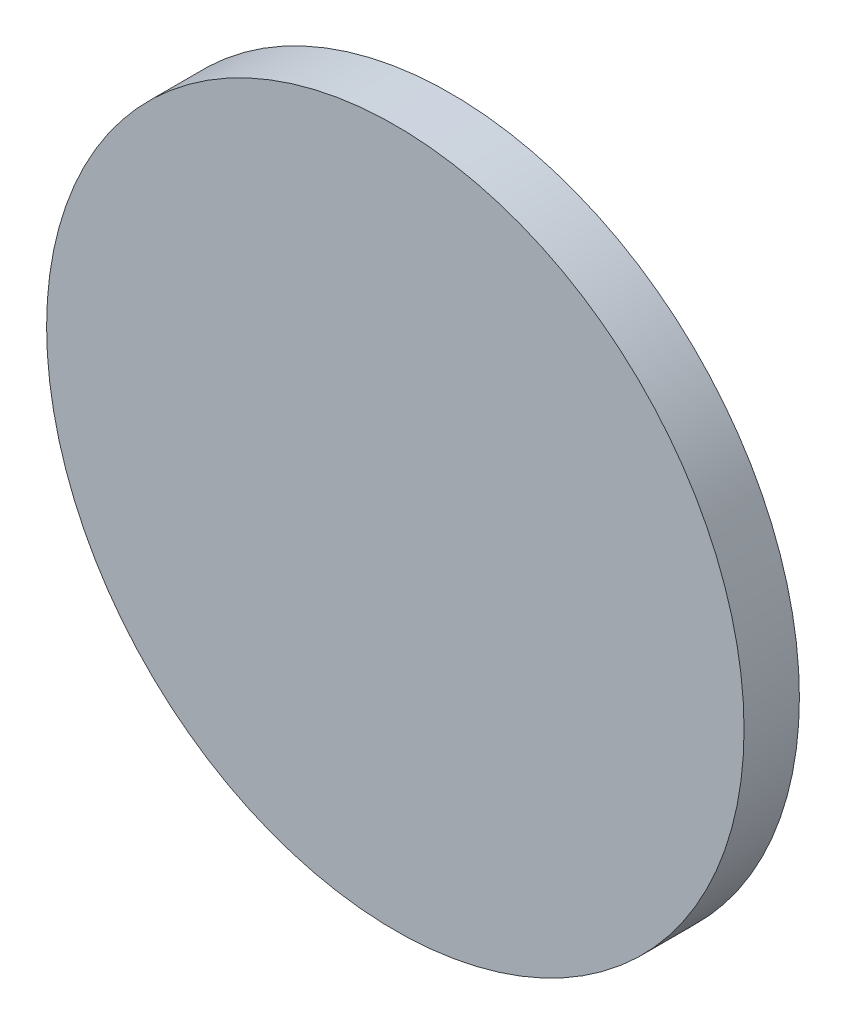
SolidWorks part; units mm, degrees
ref_plane "Front Plane" through (0, 0, 0) normal (0, 0, 1) x (1, 0, 0)
ref_plane "Top Plane" through (0, 0, 0) normal (0, 1, 0) x (1, 0, 0)
ref_plane "Right Plane" through (0, 0, 0) normal (1, 0, 0) x (0, 0, -1)
sketch "CurveSketch" plane through (0, 0, 0) normal (0, 0, 1) x (1, 0, 0)
  circle A0 centre (-3.719, 5.173) radius 73.913
  dimension "D1" = 73.913
extrude "CurveBoss" add sketch "CurveSketch" along normal blind 11.731
